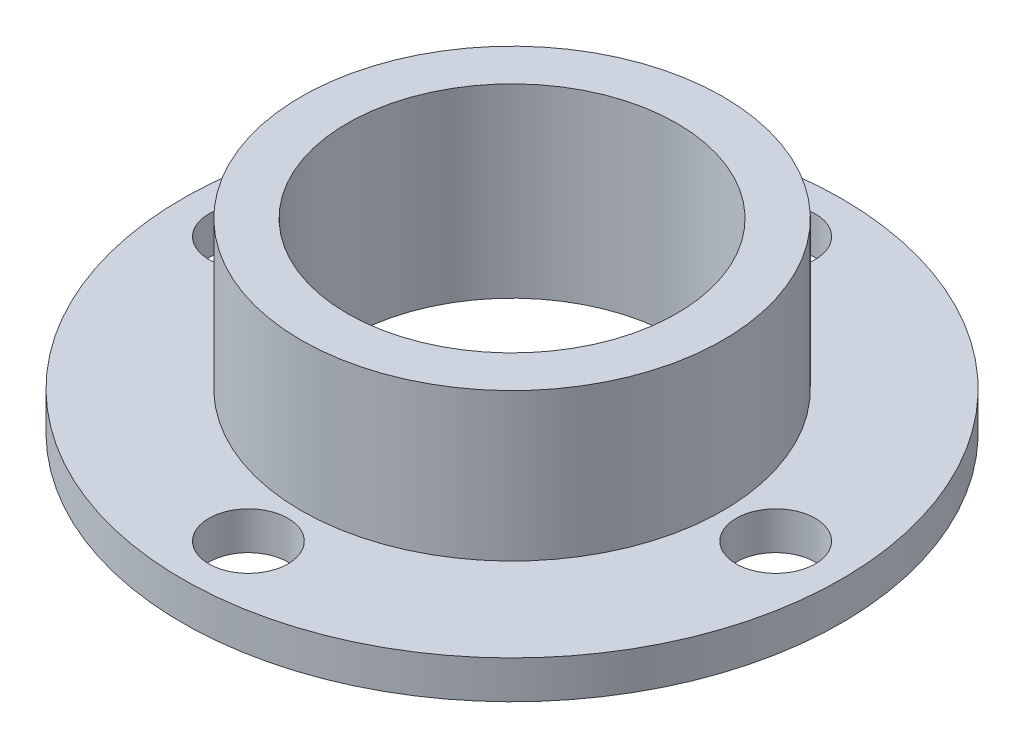
SolidWorks part; units mm, degrees
ref_plane "前视基准面" through (0, 0, 0) normal (0, 0, 1) x (1, 0, 0)
ref_plane "上视基准面" through (0, 0, 0) normal (0, 1, 0) x (1, 0, 0)
ref_plane "右视基准面" through (0, 0, 0) normal (1, 0, 0) x (0, 0, -1)
other "Configuration Table"
sketch "草图1" plane through (0, 0, 0) normal (0, 1, 0) x (1, 0, 0)
  circle A0 centre (0, 0) radius 12.5
  circle A1 centre (0, 0) radius 6.25
  circle A2 centre (0, 10) radius 1.5
  circle A3 centre (10, 0) radius 1.5
  circle A4 centre (0, -10) radius 1.5
  circle A5 centre (-10, 0) radius 1.5
  point P15 (0, 0)
  dimension "D1" = 12.5
  dimension "D3" = 25
  dimension "D4" = 3
  dimension "D2" = 10
  dimension "D5" = 4
extrude "凸台-拉伸1" add sketch "草图1" along normal blind 1.44
sketch "草图2" plane through (0, 1.44, 0) normal (0, 1, 0) x (1, 0, 0)
  circle A0 centre (0, 0) radius 6.25
  circle A1 centre (0, 0) radius 8
  dimension "D1" = 16
extrude "凸台-拉伸2" add sketch "草图2" along normal blind 5.6
